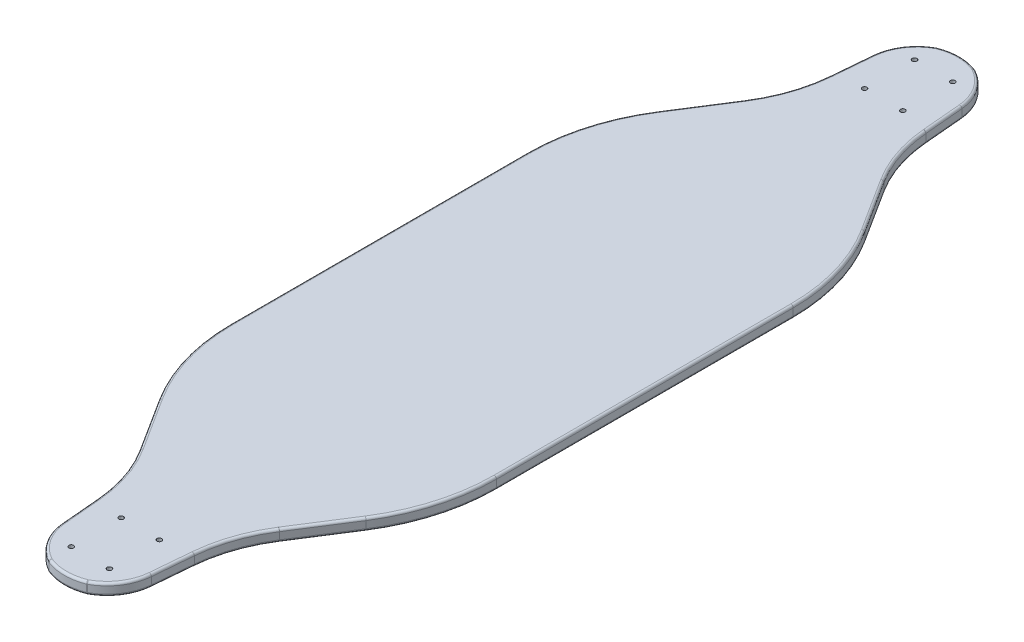
SolidWorks part; units mm, degrees
ref_plane "Front Plane" through (0, 0, 0) normal (0, 0, 1) x (1, 0, 0)
ref_plane "Top Plane" through (0, 0, 0) normal (0, 1, 0) x (1, 0, 0)
ref_plane "Right Plane" through (0, 0, 0) normal (1, 0, 0) x (0, 0, -1)
sketch "Sketch2" plane through (0, 0, 0) normal (0, 1, 0) x (1, 0, 0)
  line L0 (0, -6.985) -> (0, 6.985) construction
  line L1 (-20.6375, 26.9875) -> (20.6375, -26.9875) construction
  circle A0 centre (-20.6375, 26.9875) radius 2.54
  circle A1 centre (-20.6375, -26.9875) radius 2.54
  circle A2 centre (20.6375, -26.9875) radius 2.54
  circle A3 centre (20.6375, 26.9875) radius 2.54
  dimension "D2" = 5.08
  dimension "D1" = 53.975
  dimension "D3" = 41.275
sketch "Sketch1" plane through (0, 0, 0) normal (0, 1, 0) x (1, 0, 0)
  line L0 (-48.26, 9.255) -> (-51.9893, -33.3705)
  line L2 (-75.2765, -101.9725) -> (-111.6871, -159.1258)
  line L3 (-143.51, -268.3051) -> (-143.51, -588.9449)
  line L4 (0, -6.985) -> (0, 6.985) construction
  line L5 (143.51, -268.3051) -> (143.51, -588.9449)
  line L6 (75.2765, -101.9725) -> (111.6871, -159.1258)
  line L7 (48.26, 9.255) -> (51.9893, -33.3705)
  line L8 (-143.51, -428.625) -> (143.51, -428.625) construction
  line L18 (48.26, -866.505) -> (51.9893, -823.8795)
  line L19 (75.2765, -755.2775) -> (111.6871, -698.1242)
  line L20 (-75.2765, -755.2775) -> (-111.6871, -698.1242)
  line L21 (-48.26, -866.505) -> (-51.9893, -823.8795)
  arc A1 (-111.6871, -159.1258) -> (-143.51, -268.3051) centre (59.69, -268.3051) ccw
  arc A2 (-51.9893, -33.3705) -> (-75.2765, -101.9725) centre (-203.8093, -20.088) cw
  arc A3 (51.9893, -33.3705) -> (75.2765, -101.9725) centre (203.8093, -20.088) ccw
  arc A4 (111.6871, -159.1258) -> (143.51, -268.3051) centre (-59.69, -268.3051) cw
  arc A10 (-20.9799, 50.9326) -> (-48.26, 9.255) centre (4.2331, 4.6625) ccw
  arc A11 (20.9799, 50.9326) -> (48.26, 9.255) centre (-4.2331, 4.6625) cw
  arc A15 (20.2772, 51.2615) -> (-20.2772, 51.2615) centre (0, 0) ccw
  arc A16 (-20.2772, -908.5115) -> (-20.9799, -908.1826) centre (-17.9415, -902.6067) cw
  arc A25 (20.9799, 50.9326) -> (20.2772, 51.2615) centre (17.9415, 45.3567) ccw
  arc A26 (-20.2772, 51.2615) -> (-20.9799, 50.9326) centre (-17.9415, 45.3567) ccw
  arc A27 (20.9799, -908.1826) -> (20.2772, -908.5115) centre (17.9415, -902.6067) cw
  arc A28 (20.2772, -908.5115) -> (-20.2772, -908.5115) centre (0, -857.25) cw
  arc A29 (20.9799, -908.1826) -> (48.26, -866.505) centre (-4.2331, -861.9125) ccw
  arc A30 (-20.9799, -908.1826) -> (-48.26, -866.505) centre (4.2331, -861.9125) cw
  arc A31 (111.6871, -698.1242) -> (143.51, -588.9449) centre (-59.69, -588.9449) ccw
  arc A32 (51.9893, -823.8795) -> (75.2765, -755.2775) centre (203.8093, -837.162) cw
  arc A33 (-51.9893, -823.8795) -> (-75.2765, -755.2775) centre (-203.8093, -837.162) ccw
  arc A34 (-111.6871, -698.1242) -> (-143.51, -588.9449) centre (59.69, -588.9449) cw
  point P1 (0, 55.1263)
  point P2 (-20.6375, 51.1175)
  point P36 (0, 57.1858)
  point P38 (-43.4975, 26.9875)
  point P39 (0, 57.1858)
  point P43 (20.6375, 51.1175)
  point P51 (-20.6375, 51.1175)
  point P59 (0, -908.0142)
  point P60 (0, -914.4358)
  point P61 (-43.4975, -884.2375)
  point P62 (-20.6375, -908.3675)
  point P63 (0, -912.3763)
  point P64 (0, 50.7642)
  dimension "D1" = 22.86
  dimension "D2" = 203.2
  dimension "D5" = 152.4
  dimension "D4" = 6.35
  dimension "D6" = 65
  dimension "D7" = 96.52
  dimension "D8" = 24.13
extrude "Boss-Extrude1" add sketch "Sketch1" along normal mid plane 12.7
ref_plane "Plane1" through (0, 0, 428.625) normal (0, 0, 1) x (1, 0, 0)
fillet "Fillet1" radius 2.54 56 edges at (-135.3921, -6.35, 645.8062) (-143.51, -6.35, 428.625) (-135.3921, -6.35, 211.4438) (-93.4818, -6.35, 130.5491) (-59.4972, -6.35, 69.0754) (-50.1246, -6.35, 12.0578) (-50.1246, -6.35, 845.1922) (-59.4972, -6.35, 788.1746) (59.4972, -6.35, 788.1746) (143.51, -6.35, 428.625) (135.3921, -6.35, 211.4438) (93.4818, -6.35, 130.5491) (59.4972, -6.35, 69.0754) (50.1246, -6.35, 12.0578) (-50.1246, 6.35, 845.1922) (-59.4972, 6.35, 788.1746) (59.4972, 6.35, 788.1746) (143.51, 6.35, 428.625) (135.3921, 6.35, 211.4438) (93.4818, 6.35, 130.5491) (59.4972, 6.35, 69.0754) (50.1246, 6.35, 12.0578) (-135.3921, 6.35, 645.8062) (-143.51, 6.35, 428.625) (-135.3921, 6.35, 211.4438) (-93.4818, 6.35, 130.5491) (-59.4972, 6.35, 69.0754) (-50.1246, 6.35, 12.0578) (-39.8556, -6.35, -33.5208) (39.8556, -6.35, -33.5208) (39.8556, 6.35, -33.5208) (-39.8556, 6.35, -33.5208) (20.6336, -6.35, -51.1078) (0, -6.35, -55.1263) (-20.6336, -6.35, -51.1078) (-93.4818, -6.35, 726.7009) (-39.8556, -6.35, 890.7708) (-20.6336, -6.35, 908.3578) (0, -6.35, 912.3763) (20.6336, -6.35, 908.3578) (39.8556, -6.35, 890.7708) (50.1246, -6.35, 845.1922) (93.4818, -6.35, 726.7009) (135.3921, -6.35, 645.8062) (-20.6336, 6.35, -51.1078) (0, 6.35, -55.1263) (20.6336, 6.35, -51.1078) (135.3921, 6.35, 645.8062) (93.4818, 6.35, 726.7009) (50.1246, 6.35, 845.1922) (39.8556, 6.35, 890.7708) (20.6336, 6.35, 908.3578) (0, 6.35, 912.3763) (-20.6336, 6.35, 908.3578) (-39.8556, 6.35, 890.7708) (-93.4818, 6.35, 726.7009)
extrude "Cut-Extrude4" cut sketch "Sketch2" along normal through all both and the other way through all
mirror "Mirror1" about plane through (0, 0, 428.625) normal (0, 0, 1) of "Cut-Extrude4"
